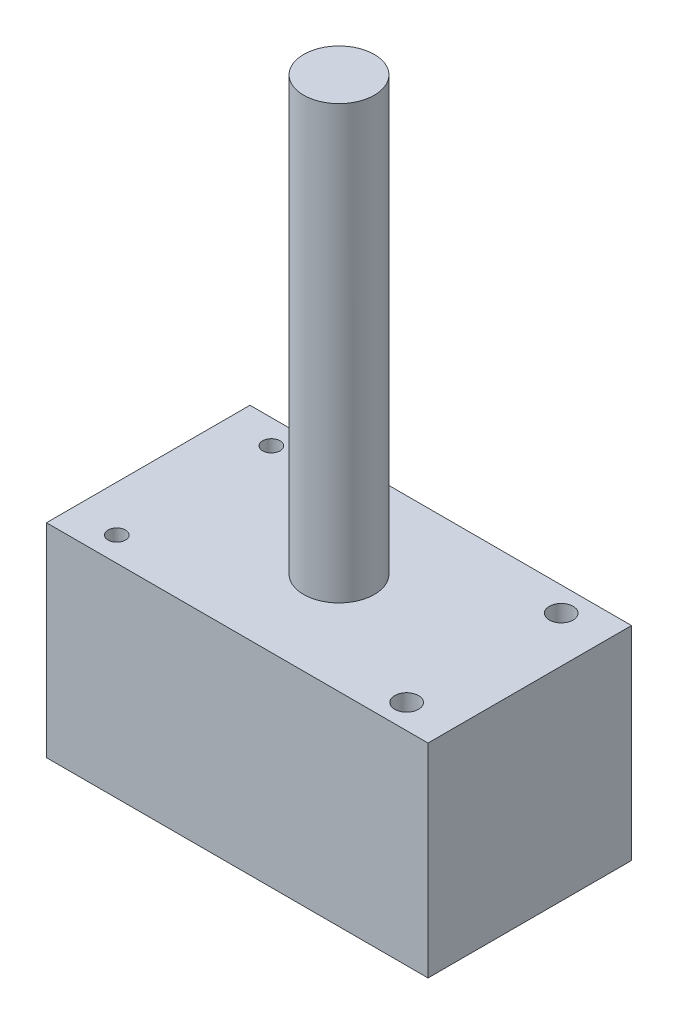
SolidWorks part; units mm, degrees
ref_plane "前视基准面" through (0, 0, 0) normal (0, 0, 1) x (1, 0, 0)
ref_plane "上视基准面" through (0, 0, 0) normal (0, 1, 0) x (1, 0, 0)
ref_plane "右视基准面" through (0, 0, 0) normal (1, 0, 0) x (0, 0, -1)
other "Configuration Table"
sketch "01_Housing_Profile" plane through (0, 0, 0) normal (0, 1, 0) x (1, 0, 0)
  line L1 (-67.5, -36) -> (67.5, -36)
  line L2 (-67.5, -36) -> (-67.5, 36)
  line L3 (-67.5, 36) -> (67.5, 36)
  line L4 (67.5, -36) -> (67.5, 36)
  line L5 (-67.5, -36) -> (67.5, 36) construction
  line L6 (-67.5, 36) -> (67.5, -36) construction
  circle A0 centre (-51.2803, -27.3495) radius 3.0905
  circle A1 centre (51.2803, -27.3495) radius 4.2197
  circle A2 centre (-51.2803, 27.3495) radius 3.0905
  circle A3 centre (51.2803, 27.3495) radius 4.2197
  point P0 (0, 0)
extrude "01_Housing_Block" add sketch "01_Housing_Profile" along normal blind 72
sketch "03_Output_Shaft_Profile" plane through (0, 0, 0) normal (0, 1, 0) x (1, 0, 0)
  circle A0 centre (0, 0) radius 12.5
extrude "03_Output_Shaft" add sketch "03_Output_Shaft_Profile" along normal blind 225
